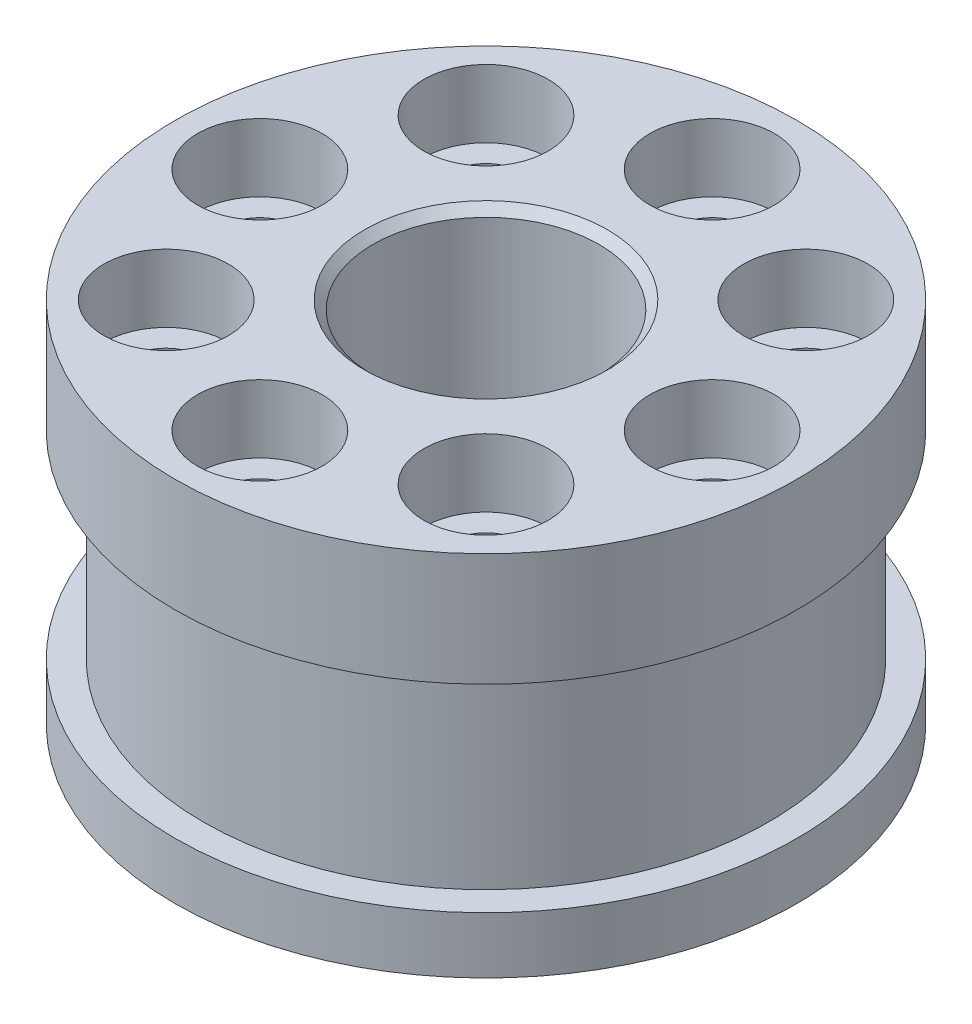
SolidWorks part; units mm, degrees
ref_plane "Front Plane" through (0, 0, 0) normal (0, 0, 1) x (1, 0, 0)
ref_plane "Top Plane" through (0, 0, 0) normal (0, 1, 0) x (1, 0, 0)
ref_plane "Right Plane" through (0, 0, 0) normal (1, 0, 0) x (0, 0, -1)
sketch "Sketch1" plane through (0, 0, 0) normal (0, 1, 0) x (1, 0, 0)
  circle A0 centre (0, 0) radius 11
  dimension "D1" = 22
extrude "Boss-Extrude1" add sketch "Sketch1" along normal blind 13
sketch "Sketch6" plane through (0, 13, 0) normal (0, 1, 0) x (1, 0, 0)
  circle A0 centre (0, 0) radius 8
  point P5 (0, 8)
  point P11 (5.6569, 5.6569)
  point P12 (8, 0)
  point P13 (5.6569, -5.6569)
  point P14 (0, -8)
  point P15 (-5.6569, -5.6569)
  point P16 (-8, 0)
  point P17 (-5.6569, 5.6569)
  dimension "D1" = 16
  dimension "D2" = 8
hole_wizard "CBORE for M2 Hex Socket Head Cap Screw1" positions "Sketch6" profile "Sketch7" counterbore size "M2" standard "DIN" end condition through all
sketch "Sketch7" plane through (-5.6569, 13, -5.6569) normal (1, 0, 0) x (0, 0, 1)
  line L0 (0, 0) -> (0, 13)
  line L1 (0, 13) -> (1.3, 13)
  line L3 (1.3, 13) -> (1.3, 2.4)
  line L4 (1.3, 2.4) -> (2.2, 2.4)
  line L5 (2.2, 2.4) -> (2.2, 0)
  line L7 (2.2, 0) -> (0, 0)
  line L11 (0, -6.35) -> (0, 107.95) construction
  dimension "Thru Hole Dia." = 2.6
  dimension "Thru Hole Depth" = 13
  dimension "C'Bore Dia." = 4.4
  dimension "C'Bore Depth" = 2.4
sketch "Sketch8" plane through (0, 0, 0) normal (0, -1, 0) x (1, 0, 0)
  circle A0 centre (0, 0) radius 10
  circle A1 centre (0, 0) radius 11 construction
  circle A2 centre (0, 0) radius 11
  dimension "D1" = 20
extrude "Cut-Extrude1" cut sketch "Sketch8" against normal blind 7 from offset 2 offset against normal yes
sketch "Sketch11" plane through (0, 0, 0) normal (0, -1, 0) x (-1, 0, 0)
  point P0 (0, 0)
hole_wizard "Ø8.0mm Dowel Hole1" positions "Sketch11" profile "Sketch12" hole size "Ø8.0" standard "DIN" end condition through all
sketch "Sketch12" plane through (0, 0, 0) normal (1, 0, 0) x (0, 0, -1)
  line L0 (0, 0) -> (0, 13)
  line L1 (0, 13) -> (4.3, 13)
  line L2 (4, 12.7) -> (4, 0.3)
  line L3 (4, 0.3) -> (4.3, 0)
  line L5 (4.3, 0) -> (0, 0)
  line L6 (-4, 0.3) -> (-4.3, 0) construction
  line L7 (4.3, 13) -> (4, 12.7)
  line L8 (-4.3, 13) -> (-4, 12.7) construction
  line L11 (0, -6.35) -> (0, 107.95) construction
  dimension "Thru Hole Dia." = 8
  dimension "Thru Hole Depth" = 13
  dimension "Near C'Sink Dia." = 8.6
  dimension "Near C'Sink Angle" = 90
  dimension "Far C'Sink Dia." = 8.6
  dimension "Far C'Sink Angle" = 90
